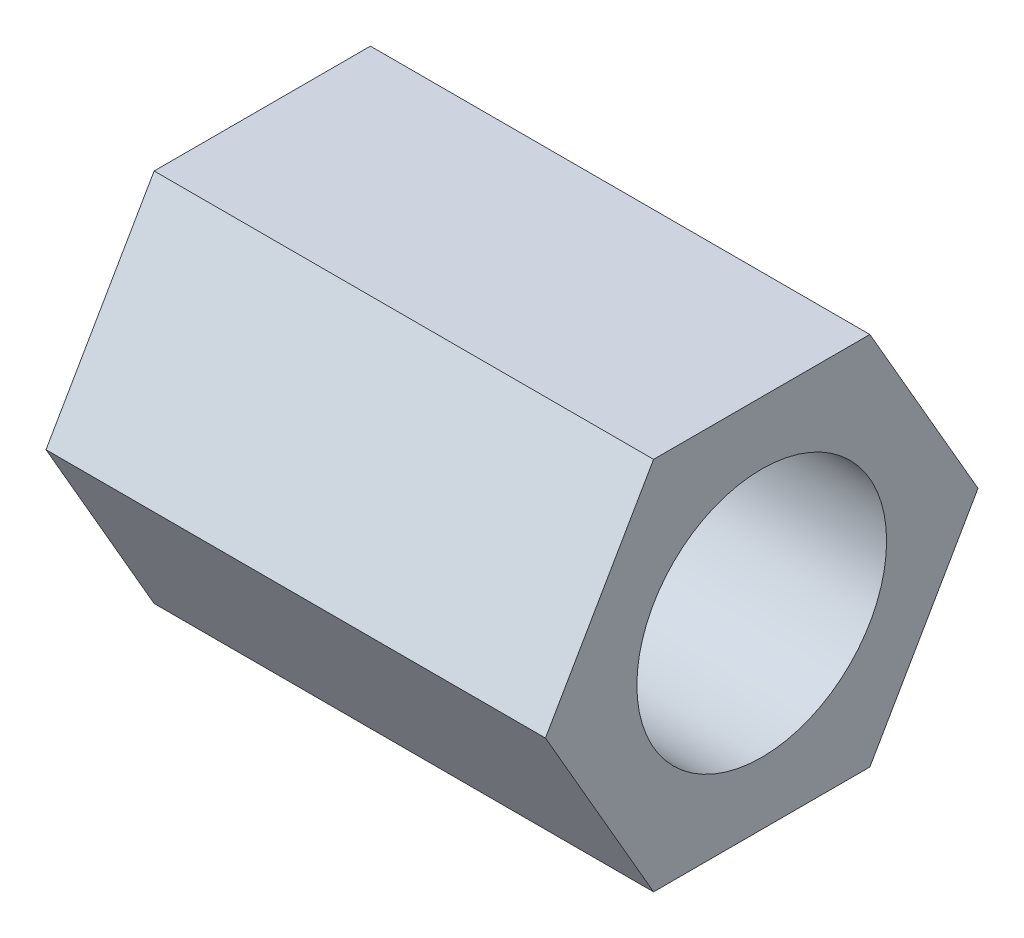
SolidWorks part; units mm, degrees
ref_plane "前视基准面" through (0, 0, 0) normal (0, 0, 1) x (1, 0, 0)
ref_plane "上视基准面" through (0, 0, 0) normal (0, 1, 0) x (1, 0, 0)
ref_plane "右视基准面" through (0, 0, 0) normal (1, 0, 0) x (0, 0, -1)
other "Configuration Table"
sketch "草图1" plane through (0, 0, 0) normal (1, 0, 0) x (0, 0, -1)
  circle A0 centre (0, 0) radius 1.5
  dimension "D1" = 3
extrude "凸台-拉伸1" add sketch "草图1" along normal blind 6
sketch "草图2" plane through (6, 0, 0) normal (1, 0, 0) x (0, 0, -1)
  line L1 (2.5981, 0) -> (1.299, 2.25)
  line L2 (1.299, 2.25) -> (-1.299, 2.25)
  line L3 (-1.299, 2.25) -> (-2.5981, 0)
  line L4 (-2.5981, 0) -> (-1.299, -2.25)
  line L5 (-1.299, -2.25) -> (1.299, -2.25)
  line L6 (1.299, -2.25) -> (2.5981, 0)
  circle A0 centre (0, 0) radius 2.25 construction
  dimension "D1" = 4.5
extrude "凸台-拉伸2" add sketch "草图2" along normal blind 6
sketch "草图3" plane through (12, 0, 0) normal (1, 0, 0) x (0, 0, -1)
  circle A0 centre (0, 0) radius 1.5
  dimension "D1" = 3
sketch "草图4" plane through (12, 0, 0) normal (1, 0, 0) x (0, 0, -1)
  circle A0 centre (0, 0) radius 1.5
extrude "切除-拉伸1" cut sketch "草图4" against normal blind 7
sketch "草图5" plane through (0, 0, 0) normal (-1, 0, 0) x (0, 0, 1)
  circle A0 centre (0, 0) radius 2.9027
extrude "切除-拉伸2" cut sketch "草图5" against normal blind 6
